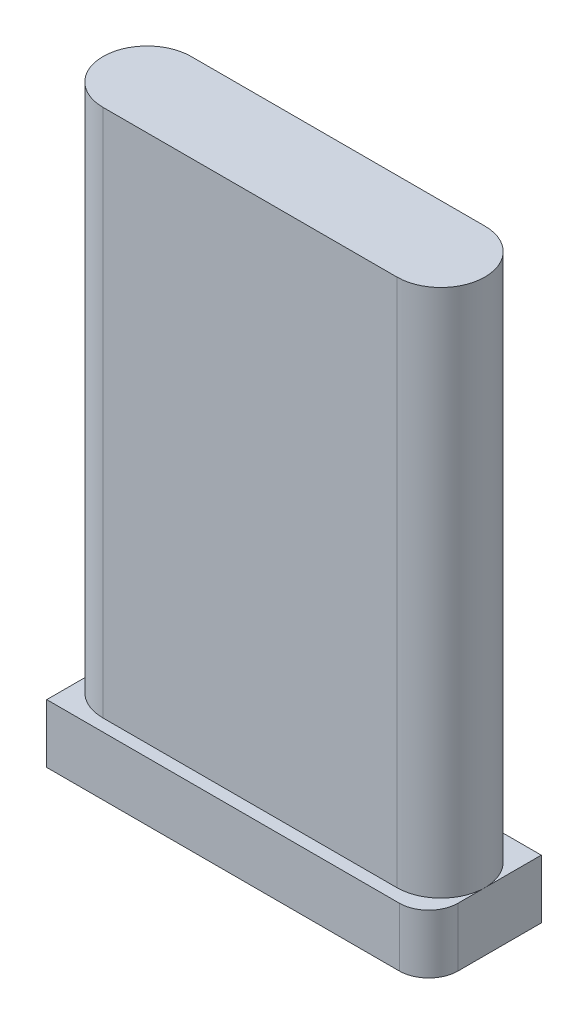
SolidWorks part; units mm, degrees
ref_plane "前视基准面" through (0, 0, 0) normal (0, 0, 1) x (1, 0, 0)
ref_plane "上视基准面" through (0, 0, 0) normal (0, 1, 0) x (1, 0, 0)
ref_plane "右视基准面" through (0, 0, 0) normal (1, 0, 0) x (0, 0, -1)
other "Configuration Table"
sketch "草图1" plane through (0, 0, 0) normal (0, 1, 0) x (1, 0, 0)
  line L0 (-5, 0) -> (5, 0) construction
  line L1 (-5, 1.5) -> (5, 1.5)
  line L2 (-5, -1.5) -> (5, -1.5)
  arc A0 (-5, 1.5) -> (-5, -1.5) centre (-5, 0) ccw
  arc A1 (5, -1.5) -> (5, 1.5) centre (5, 0) ccw
  point P2 (0, 0)
  dimension "D2" = 1.5
  dimension "D1" = 10
extrude "凸台-拉伸1" add sketch "草图1" along normal blind 18
sketch "草图2" plane through (0, 0, 0) normal (0, -1, 0) x (1, 0, 0)
  line L1 (-6.5, 1.916) -> (6.5, 1.916)
  line L2 (-6.5, 1.916) -> (-6.5, -1.916)
  line L3 (-6.5, -1.916) -> (6.5, -1.916)
  line L4 (6.5, 1.916) -> (6.5, -1.916)
  line L5 (-6.5, 1.916) -> (6.5, -1.916) construction
  line L6 (-6.5, -1.916) -> (6.5, 1.916) construction
  arc A0 (5, -1.5) -> (5, 1.5) centre (5, 0) ccw construction
  point P0 (0, 0)
extrude "凸台-拉伸2" add sketch "草图2" along normal blind 2
sketch "草图5" plane through (0, -2, 0) normal (0, -1, 0) x (1, 0, 0)
  text T0 "db. James YasR " font "黑体" height 1
extrude "切除-拉伸1" cut sketch "草图5" against normal blind 0.5
fillet "圆角3" radius 1 1 edges at (6.5, -1, 1.916)
fillet "圆角4" radius 1 1 edges at (-6.5, -1, -1.916)
